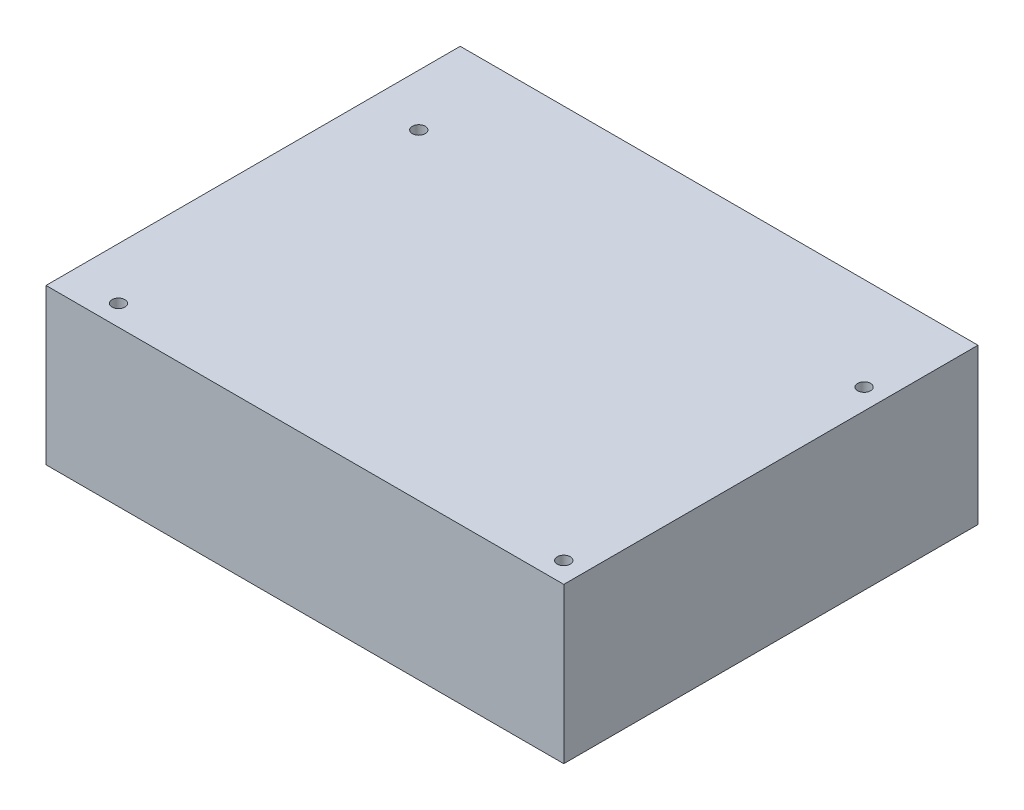
SolidWorks part; units mm, degrees
material "聚脂树脂"
ref_plane "前视基准面" through (0, 0, 0) normal (0, 0, 1) x (1, 0, 0)
ref_plane "上视基准面" through (0, 0, 0) normal (0, 1, 0) x (1, 0, 0)
ref_plane "右视基准面" through (0, 0, 0) normal (1, 0, 0) x (0, 0, -1)
other "Configuration Table"
sketch "草图1" plane through (0, 0, 0) normal (0, 1, 0) x (1, 0, 0)
  line L1 (-50, -40) -> (50, -40)
  line L2 (-50, -40) -> (-50, 40)
  line L3 (-50, 40) -> (50, 40)
  line L4 (50, -40) -> (50, 40)
  line L5 (-50, -40) -> (50, 40) construction
  line L6 (-50, 40) -> (50, -40) construction
  point P0 (0, 0)
  dimension "D1" = 100
  dimension "D2" = 80
extrude "凸台-拉伸1" add sketch "草图1" along normal blind 30
sketch "草图2" plane through (0, 0, -40) normal (0, 0, -1) x (-1, 0, 0)
  line L0 (-50, 30) -> (-50, 0) construction
  line L1 (-50, 0) -> (50, 0) construction
  circle A0 centre (-41, 9) radius 5
  dimension "D1" = 10
  dimension "D2" = 9
  dimension "D3" = 9
extrude "切除-拉伸1" cut sketch "草图2" against normal blind 5
sketch "草图3" plane through (0, 0, -40) normal (0, 0, -1) x (-1, 0, 0)
  line L0 (-50, 0) -> (50, 0) construction
  line L1 (-20, 15) -> (-5, 15)
  line L2 (-20, 15) -> (-20, 21)
  line L3 (-20, 21) -> (-5, 21)
  line L4 (-5, 15) -> (-5, 21)
  line L5 (-20, 15) -> (-5, 21) construction
  line L6 (-20, 21) -> (-5, 15) construction
  line L7 (5, 15) -> (20, 15)
  line L8 (5, 15) -> (5, 21)
  line L9 (5, 21) -> (20, 21)
  line L10 (20, 15) -> (20, 21)
  line L11 (5, 15) -> (20, 21) construction
  line L12 (5, 21) -> (20, 15) construction
  line L13 (-20, 3) -> (-5, 3)
  line L14 (-20, 3) -> (-20, 9)
  line L15 (-20, 9) -> (-5, 9)
  line L16 (-5, 3) -> (-5, 9)
  line L17 (-20, 3) -> (-5, 9) construction
  line L18 (-20, 9) -> (-5, 3) construction
  line L19 (5, 3) -> (20, 3)
  line L20 (5, 3) -> (5, 9)
  line L21 (5, 9) -> (20, 9)
  line L22 (20, 3) -> (20, 9)
  line L23 (5, 3) -> (20, 9) construction
  line L24 (5, 9) -> (20, 3) construction
  line L25 (-50, 30) -> (-50, 0) construction
  point P0 (-12.5, 18)
  point P5 (12.5, 18)
  point P10 (-12.5, 6)
  point P15 (12.5, 6)
  dimension "D1" = 15
  dimension "D2" = 15
  dimension "D3" = 15
  dimension "D4" = 15
  dimension "D5" = 6
  dimension "D6" = 6
  dimension "D7" = 6
  dimension "D8" = 6
  dimension "D9" = 6
  dimension "D10" = 6
  dimension "D11" = 10
  dimension "D12" = 10
  dimension "D13" = 3
  dimension "D14" = 30
  dimension "D15" = 30
  dimension "D16" = 3
extrude "切除-拉伸2" cut sketch "草图3" against normal blind 5
sketch "草图5" plane through (0, 0, 0) normal (0, -1, 0) x (1, 0, 0)
  line L0 (-50, 40) -> (50, 40) construction
  line L1 (50, 40) -> (50, -40) construction
  circle A0 centre (46, 36) radius 1.25
  circle A1 centre (-40, 36) radius 1.25
  circle A2 centre (-40, -22) radius 1.25
  circle A3 centre (46, -22) radius 1.25
  dimension "D1" = 2.5
  dimension "D2" = 2.5
  dimension "D3" = 4
  dimension "D5" = 4
  dimension "D6" = 86
  dimension "D7" = 2.5
  dimension "D8" = 2.5
  dimension "D9" = 4
  dimension "D10" = 58
  dimension "D11" = 86
  dimension "D12" = 58
  dimension "D4" = 4
extrude "切除-拉伸3" cut sketch "草图5" against normal blind 51
